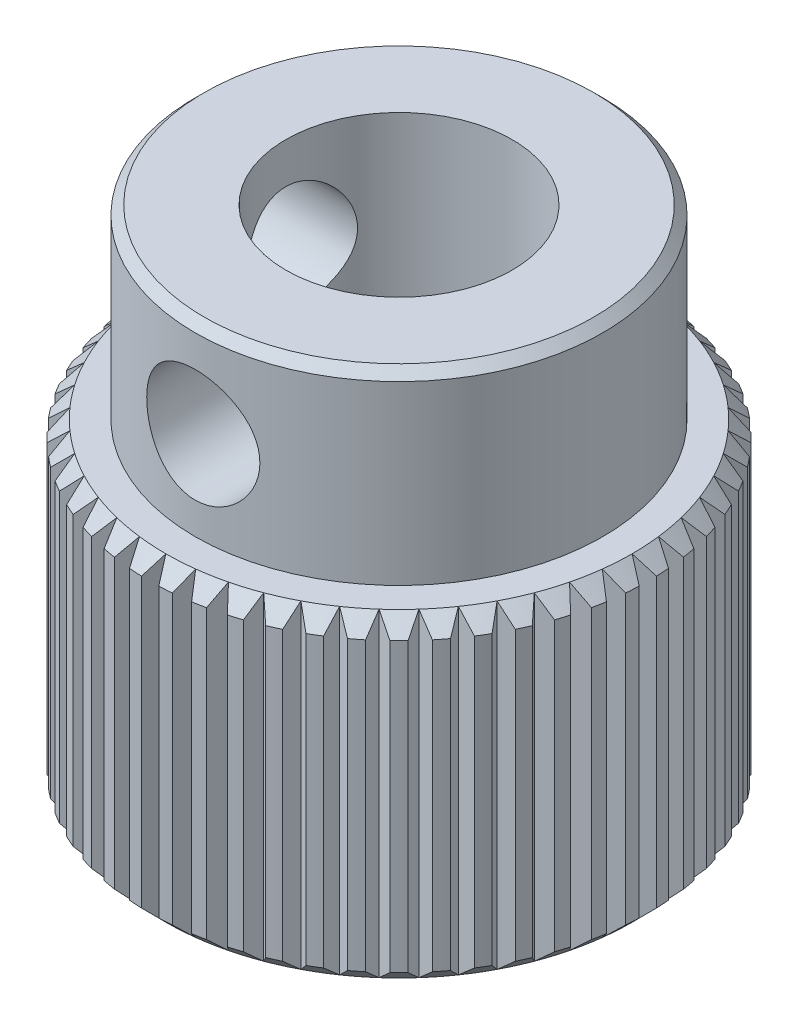
SolidWorks part; units mm, degrees
ref_plane "Front Plane" through (0, 0, 0) normal (0, 0, 1) x (1, 0, 0)
ref_plane "Top Plane" through (0, 0, 0) normal (0, 1, 0) x (1, 0, 0)
ref_plane "Right Plane" through (0, 0, 0) normal (1, 0, 0) x (0, 0, -1)
sketch "Sketch1" plane through (0, 0, 0) normal (0, 1, 0) x (1, 0, 0)
  circle A0 centre (0, 0) radius 5.5
  dimension "D1" = 11
extrude "Boss-Extrude1" add sketch "Sketch1" along normal mid plane 11.15
sketch "Sketch3" plane through (0, 5.575, 0) normal (0, 1, 0) x (1, 0, 0)
  circle A0 centre (0, 0) radius 4.5
  dimension "D1" = 9
extrude "Cut-Extrude2" cut sketch "Sketch3" against normal blind 4.1 flip side to cut
chamfer "Chamfer1" distance 0.35 angle 45 2 edges at (0, -5.575, 5.5) (0, 1.475, 5.5)
chamfer "Chamfer2" distance 0.2 angle 45 1 edges at (0, 5.575, 4.5)
sketch "Sketch2" plane through (0, 5.575, 0) normal (0, 1, 0) x (1, 0, 0)
  line L0 (0, 5.5) -> (0, 0) construction
  line L1 (-0.1904, 5.4967) -> (0, 5.15)
  line L2 (0, 5.15) -> (0.1904, 5.4967)
  line L4 (0.4736, 5.4796) -> (0.6208, 5.1125)
  line L5 (0.6208, 5.1125) -> (0.8515, 5.4337)
  line L6 (1.1306, 5.3825) -> (1.2325, 5.0004)
  line L7 (1.2325, 5.0004) -> (1.5003, 5.2914)
  line L8 (1.7711, 5.207) -> (1.8262, 4.8153)
  line L9 (1.8262, 4.8153) -> (2.1272, 5.072)
  line L10 (2.3859, 4.9556) -> (2.3933, 4.5601)
  line L11 (2.3933, 4.5601) -> (2.723, 4.7786)
  line L12 (2.9658, 4.6318) -> (2.9255, 4.2384)
  line L13 (2.9255, 4.2384) -> (3.2792, 4.4155)
  line L14 (3.5025, 4.2406) -> (3.4151, 3.8548)
  line L15 (3.4151, 3.8548) -> (3.7875, 3.9881)
  line L16 (3.9881, 3.7875) -> (3.8548, 3.4151)
  line L17 (3.8548, 3.4151) -> (4.2406, 3.5025)
  line L18 (4.4155, 3.2792) -> (4.2384, 2.9255)
  line L19 (4.2384, 2.9255) -> (4.6318, 2.9658)
  line L20 (4.7786, 2.723) -> (4.5601, 2.3933)
  line L21 (4.5601, 2.3933) -> (4.9556, 2.3859)
  line L22 (5.072, 2.1272) -> (4.8153, 1.8262)
  line L23 (4.8153, 1.8262) -> (5.207, 1.7711)
  line L24 (5.2914, 1.5003) -> (5.0004, 1.2325)
  line L25 (5.0004, 1.2325) -> (5.3825, 1.1306)
  line L26 (5.4337, 0.8515) -> (5.1125, 0.6208)
  line L27 (5.1125, 0.6208) -> (5.4796, 0.4736)
  line L28 (5.4967, 0.1904) -> (5.15, 0)
  line L29 (5.15, 0) -> (5.4967, -0.1904)
  line L30 (5.4796, -0.4736) -> (5.1125, -0.6208)
  line L31 (5.1125, -0.6208) -> (5.4337, -0.8515)
  line L32 (5.3825, -1.1306) -> (5.0004, -1.2325)
  line L33 (5.0004, -1.2325) -> (5.2914, -1.5003)
  line L34 (5.207, -1.7711) -> (4.8153, -1.8262)
  line L35 (4.8153, -1.8262) -> (5.072, -2.1272)
  line L36 (4.9556, -2.3859) -> (4.5601, -2.3933)
  line L37 (4.5601, -2.3933) -> (4.7786, -2.723)
  line L38 (4.6318, -2.9658) -> (4.2384, -2.9255)
  line L39 (4.2384, -2.9255) -> (4.4155, -3.2792)
  line L40 (4.2406, -3.5025) -> (3.8548, -3.4151)
  line L41 (3.8548, -3.4151) -> (3.9881, -3.7875)
  line L42 (3.7875, -3.9881) -> (3.4151, -3.8548)
  line L43 (3.4151, -3.8548) -> (3.5025, -4.2406)
  line L44 (3.2792, -4.4155) -> (2.9255, -4.2384)
  line L45 (2.9255, -4.2384) -> (2.9658, -4.6318)
  line L46 (2.723, -4.7786) -> (2.3933, -4.5601)
  line L47 (2.3933, -4.5601) -> (2.3859, -4.9556)
  line L48 (2.1272, -5.072) -> (1.8262, -4.8153)
  line L49 (1.8262, -4.8153) -> (1.7711, -5.207)
  line L50 (1.5003, -5.2914) -> (1.2325, -5.0004)
  line L51 (1.2325, -5.0004) -> (1.1306, -5.3825)
  line L52 (0.8515, -5.4337) -> (0.6208, -5.1125)
  line L53 (0.6208, -5.1125) -> (0.4736, -5.4796)
  line L54 (0.1904, -5.4967) -> (0, -5.15)
  line L55 (0, -5.15) -> (-0.1904, -5.4967)
  line L56 (-0.4736, -5.4796) -> (-0.6208, -5.1125)
  line L57 (-0.6208, -5.1125) -> (-0.8515, -5.4337)
  line L58 (-1.1306, -5.3825) -> (-1.2325, -5.0004)
  line L59 (-1.2325, -5.0004) -> (-1.5003, -5.2914)
  line L60 (-1.7711, -5.207) -> (-1.8262, -4.8153)
  line L61 (-1.8262, -4.8153) -> (-2.1272, -5.072)
  line L62 (-2.3859, -4.9556) -> (-2.3933, -4.5601)
  line L63 (-2.3933, -4.5601) -> (-2.723, -4.7786)
  line L64 (-2.9658, -4.6318) -> (-2.9255, -4.2384)
  line L65 (-2.9255, -4.2384) -> (-3.2792, -4.4155)
  line L66 (-3.5025, -4.2406) -> (-3.4151, -3.8548)
  line L67 (-3.4151, -3.8548) -> (-3.7875, -3.9881)
  line L68 (-3.9881, -3.7875) -> (-3.8548, -3.4151)
  line L69 (-3.8548, -3.4151) -> (-4.2406, -3.5025)
  line L70 (-4.4155, -3.2792) -> (-4.2384, -2.9255)
  line L71 (-4.2384, -2.9255) -> (-4.6318, -2.9658)
  line L72 (-4.7786, -2.723) -> (-4.5601, -2.3933)
  line L73 (-4.5601, -2.3933) -> (-4.9556, -2.3859)
  line L74 (-5.072, -2.1272) -> (-4.8153, -1.8262)
  line L75 (-4.8153, -1.8262) -> (-5.207, -1.7711)
  line L76 (-5.2914, -1.5003) -> (-5.0004, -1.2325)
  line L77 (-5.0004, -1.2325) -> (-5.3825, -1.1306)
  line L78 (-5.4337, -0.8515) -> (-5.1125, -0.6208)
  line L79 (-5.1125, -0.6208) -> (-5.4796, -0.4736)
  line L80 (-5.4967, -0.1904) -> (-5.15, 0)
  line L81 (-5.15, 0) -> (-5.4967, 0.1904)
  line L82 (-5.4796, 0.4736) -> (-5.1125, 0.6208)
  line L83 (-5.1125, 0.6208) -> (-5.4337, 0.8515)
  line L84 (-5.3825, 1.1306) -> (-5.0004, 1.2325)
  line L85 (-5.0004, 1.2325) -> (-5.2914, 1.5003)
  line L86 (-5.207, 1.7711) -> (-4.8153, 1.8262)
  line L87 (-4.8153, 1.8262) -> (-5.072, 2.1272)
  line L88 (-4.9556, 2.3859) -> (-4.5601, 2.3933)
  line L89 (-4.5601, 2.3933) -> (-4.7786, 2.723)
  line L90 (-4.6318, 2.9658) -> (-4.2384, 2.9255)
  line L91 (-4.2384, 2.9255) -> (-4.4155, 3.2792)
  line L92 (-4.2406, 3.5025) -> (-3.8548, 3.4151)
  line L93 (-3.8548, 3.4151) -> (-3.9881, 3.7875)
  line L94 (-3.7875, 3.9881) -> (-3.4151, 3.8548)
  line L95 (-3.4151, 3.8548) -> (-3.5025, 4.2406)
  line L96 (-3.2792, 4.4155) -> (-2.9255, 4.2384)
  line L97 (-2.9255, 4.2384) -> (-2.9658, 4.6318)
  line L98 (-2.723, 4.7786) -> (-2.3933, 4.5601)
  line L99 (-2.3933, 4.5601) -> (-2.3859, 4.9556)
  line L100 (-2.1272, 5.072) -> (-1.8262, 4.8153)
  line L101 (-1.8262, 4.8153) -> (-1.7711, 5.207)
  line L102 (-1.5003, 5.2914) -> (-1.2325, 5.0004)
  line L103 (-1.2325, 5.0004) -> (-1.1306, 5.3825)
  line L104 (-0.8515, 5.4337) -> (-0.6208, 5.1125)
  line L105 (-0.6208, 5.1125) -> (-0.4736, 5.4796)
  line L106 (0, 0) -> (0, 5.15) construction
  line L107 (0, 0) -> (0.6208, 5.1125) construction
  arc A2 (0.8515, 5.4337) -> (0.4736, 5.4796) centre (0, 0) ccw
  arc A5 (1.5003, 5.2914) -> (1.1306, 5.3825) centre (0, 0) ccw
  arc A6 (2.1272, 5.072) -> (1.7711, 5.207) centre (0, 0) ccw
  arc A7 (2.723, 4.7786) -> (2.3859, 4.9556) centre (0, 0) ccw
  arc A8 (3.2792, 4.4155) -> (2.9658, 4.6318) centre (0, 0) ccw
  arc A9 (3.7875, 3.9881) -> (3.5025, 4.2406) centre (0, 0) ccw
  arc A10 (4.2406, 3.5025) -> (3.9881, 3.7875) centre (0, 0) ccw
  arc A11 (4.6318, 2.9658) -> (4.4155, 3.2792) centre (0, 0) ccw
  arc A12 (4.9556, 2.3859) -> (4.7786, 2.723) centre (0, 0) ccw
  arc A13 (5.207, 1.7711) -> (5.072, 2.1272) centre (0, 0) ccw
  arc A14 (5.3825, 1.1306) -> (5.2914, 1.5003) centre (0, 0) ccw
  arc A15 (5.4796, 0.4736) -> (5.4337, 0.8515) centre (0, 0) ccw
  arc A16 (5.4967, -0.1904) -> (5.4967, 0.1904) centre (0, 0) ccw
  arc A17 (5.4337, -0.8515) -> (5.4796, -0.4736) centre (0, 0) ccw
  arc A18 (5.2914, -1.5003) -> (5.3825, -1.1306) centre (0, 0) ccw
  arc A19 (5.072, -2.1272) -> (5.207, -1.7711) centre (0, 0) ccw
  arc A20 (4.7786, -2.723) -> (4.9556, -2.3859) centre (0, 0) ccw
  arc A21 (4.4155, -3.2792) -> (4.6318, -2.9658) centre (0, 0) ccw
  arc A22 (3.9881, -3.7875) -> (4.2406, -3.5025) centre (0, 0) ccw
  arc A23 (3.5025, -4.2406) -> (3.7875, -3.9881) centre (0, 0) ccw
  arc A24 (2.9658, -4.6318) -> (3.2792, -4.4155) centre (0, 0) ccw
  arc A25 (2.3859, -4.9556) -> (2.723, -4.7786) centre (0, 0) ccw
  arc A26 (1.7711, -5.207) -> (2.1272, -5.072) centre (0, 0) ccw
  arc A27 (1.1306, -5.3825) -> (1.5003, -5.2914) centre (0, 0) ccw
  arc A28 (0.4736, -5.4796) -> (0.8515, -5.4337) centre (0, 0) ccw
  arc A29 (-0.1904, -5.4967) -> (0.1904, -5.4967) centre (0, 0) ccw
  arc A30 (-0.8515, -5.4337) -> (-0.4736, -5.4796) centre (0, 0) ccw
  arc A31 (-1.5003, -5.2914) -> (-1.1306, -5.3825) centre (0, 0) ccw
  arc A32 (-2.1272, -5.072) -> (-1.7711, -5.207) centre (0, 0) ccw
  arc A33 (-2.723, -4.7786) -> (-2.3859, -4.9556) centre (0, 0) ccw
  arc A34 (-3.2792, -4.4155) -> (-2.9658, -4.6318) centre (0, 0) ccw
  arc A35 (-3.7875, -3.9881) -> (-3.5025, -4.2406) centre (0, 0) ccw
  arc A36 (-4.2406, -3.5025) -> (-3.9881, -3.7875) centre (0, 0) ccw
  arc A37 (-4.6318, -2.9658) -> (-4.4155, -3.2792) centre (0, 0) ccw
  arc A38 (-4.9556, -2.3859) -> (-4.7786, -2.723) centre (0, 0) ccw
  arc A39 (-5.207, -1.7711) -> (-5.072, -2.1272) centre (0, 0) ccw
  arc A40 (-5.3825, -1.1306) -> (-5.2914, -1.5003) centre (0, 0) ccw
  arc A41 (-5.4796, -0.4736) -> (-5.4337, -0.8515) centre (0, 0) ccw
  arc A42 (-5.4967, 0.1904) -> (-5.4967, -0.1904) centre (0, 0) ccw
  arc A43 (-5.4337, 0.8515) -> (-5.4796, 0.4736) centre (0, 0) ccw
  arc A44 (-5.2914, 1.5003) -> (-5.3825, 1.1306) centre (0, 0) ccw
  arc A45 (-5.072, 2.1272) -> (-5.207, 1.7711) centre (0, 0) ccw
  arc A46 (-4.7786, 2.723) -> (-4.9556, 2.3859) centre (0, 0) ccw
  arc A47 (-4.4155, 3.2792) -> (-4.6318, 2.9658) centre (0, 0) ccw
  arc A48 (-3.9881, 3.7875) -> (-4.2406, 3.5025) centre (0, 0) ccw
  arc A49 (-3.5025, 4.2406) -> (-3.7875, 3.9881) centre (0, 0) ccw
  arc A50 (-2.9658, 4.6318) -> (-3.2792, 4.4155) centre (0, 0) ccw
  arc A51 (-2.3859, 4.9556) -> (-2.723, 4.7786) centre (0, 0) ccw
  arc A52 (-1.7711, 5.207) -> (-2.1272, 5.072) centre (0, 0) ccw
  arc A53 (-1.1306, 5.3825) -> (-1.5003, 5.2914) centre (0, 0) ccw
  arc A54 (-0.4736, 5.4796) -> (-0.8515, 5.4337) centre (0, 0) ccw
  circle A55 centre (0, 0) radius 5.5 construction
  circle A58 centre (0, 0) radius 5.15 construction
  arc A59 (0.1904, 5.4967) -> (-0.1904, 5.4967) centre (0, 0) ccw
  dimension "D1" = 0.3808
  dimension "D2" = 6.923
  dimension "D4" = 52
extrude "Cut-Extrude1" cut sketch "Sketch2" against normal through all
sketch "Sketch4" plane through (0, 5.575, 0) normal (0, 1, 0) x (1, 0, 0)
  circle A0 centre (0, 0) radius 2.5
  dimension "D1" = 5
extrude "Cut-Extrude3" cut sketch "Sketch4" against normal through all
hole_wizard "M3x0.5 Tapped Hole1" positions "3DSketch1" profile "Sketch5" tap size "M3x0.5" standard "ANSI Metric"
sketch3d "3DSketch1"
  line L0 (0, 0, 0) -> (0, 3.425, 0) construction
  line L3 (0, 3.425, 0) -> (0, 3.425, 4.5) construction
  line L5 (0, 5.375, 4.5) -> (0, 1.475, 4.5) construction
  circle A0 centre (0, 5.375, 0) radius 4.5 construction
  circle A1 centre (0, 1.475, 0) radius 4.5 construction
  point P0 (0, 3.425, 4.5)
  point P16 (0, 0.875, 0)
  point P19 (0, 5.975, 0)
sketch "Sketch5" plane through (0, 3.425, 4.5) normal (1, 0, 0) x (0, -1, 0)
  line L0 (0, 0) -> (0, 2)
  line L1 (0, 2) -> (1.25, 2)
  line L2 (1.25, 2) -> (1.25, 0)
  line L5 (1.25, 0) -> (0, 0)
  line L11 (0, -6.35) -> (0, 107.95) construction
  dimension "Thru Tap Drill Dia." = 2.5
  dimension "Thru Tap Drill Depth" = 2
cosmetic thread "Hole Thread1" parameters "D2"=3
pattern_circular "CirPattern1" count 2 over 90 about axis through (0, 1.475, 0) along (0, 1, 0) of "M3x0.5 Tapped Hole1"
cosmetic thread "Hole Thread2" parameters "D2"=3
